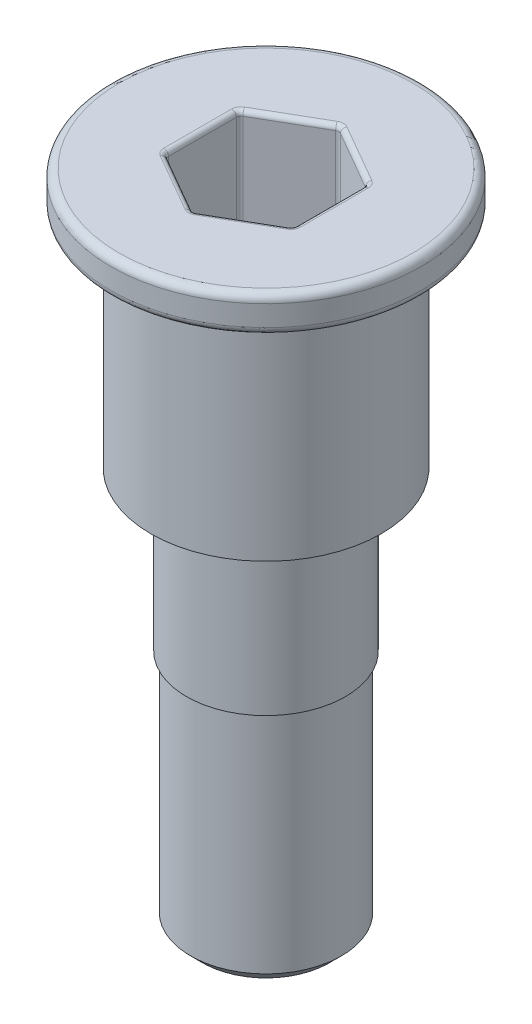
SolidWorks part; units mm, degrees
ref_plane "Plano frontal" through (0, 0, 0) normal (0, 0, 1) x (1, 0, 0)
ref_plane "Plano superior" through (0, 0, 0) normal (0, 1, 0) x (1, 0, 0)
ref_plane "Plano direito" through (0, 0, 0) normal (1, 0, 0) x (0, 0, -1)
sketch "Esboço1" plane through (0, 0, 0) normal (0, 0, 1) x (1, 0, 0)
  line L0 (0, -39.8088) -> (0, 49.1334) construction
  line L1 (0, 17.0567) -> (9.75, 17.0567)
  line L2 (9.75, 17.0567) -> (9.75, 14.7567)
  line L3 (9.75, 14.7567) -> (7.25, 14.7567)
  line L4 (7.25, 14.7567) -> (7.25, 0.7567)
  line L5 (7.25, 0.7567) -> (5, 0.7567)
  line L6 (5, 0.7567) -> (5, -9.2433)
  line L7 (5, -9.2433) -> (4.75, -9.2433)
  line L8 (4.75, -9.2433) -> (4.75, -24.2433)
  line L9 (4.75, -24.2433) -> (0, -24.2433)
  line L10 (0, 17.0567) -> (0, -24.2433)
  dimension "D1" = 4.75
  dimension "D2" = 5
  dimension "D3" = 15
  dimension "D4" = 10
  dimension "D5" = 14
  dimension "D6" = 2.3
  dimension "D7" = 7.25
  dimension "D8" = 9.75
revolve "Revolução1" add sketch "Esboço1" angle 360 about L0
fillet "Filete1" radius 0.5 2 edges at (0, 14.7567, -9.75) (0, 17.0567, -9.75)
sketch "Esboço2" plane through (0, 17.0567, 0) normal (0, 1, 0) x (1, 0, 0)
  line L1 (0, 4.6188) -> (-4, 2.3094)
  line L2 (-4, 2.3094) -> (-4, -2.3094)
  line L3 (-4, -2.3094) -> (0, -4.6188)
  line L4 (0, -4.6188) -> (4, -2.3094)
  line L5 (4, -2.3094) -> (4, 2.3094)
  line L6 (4, 2.3094) -> (0, 4.6188)
  circle A0 centre (0, 0) radius 4 construction
  dimension "D1" = 8
extrude "Corte-extrusão1" cut sketch "Esboço2" against normal blind 6.5
fillet "Filete2" radius 0.3 18 edges at (4, 17.0567, 0) (-2, 17.0567, -3.4641) (2, 17.0567, -3.4641) (-4, 17.0567, 0) (-2, 17.0567, 3.4641) (2, 17.0567, 3.4641) (2, 10.5567, 3.4641) (4, 10.5567, 0) (4, 13.8067, 2.3094) (4, 13.8067, -2.3094) (0, 13.8067, -4.6188) (-4, 13.8067, 2.3094) (-4, 13.8067, -2.3094) (0, 13.8067, 4.6188) (-2, 10.5567, 3.4641) (-4, 10.5567, 0) (2, 10.5567, -3.4641) (-2, 10.5567, -3.4641)
chamfer "Chanfro1" distance 0.75 angle 45 1 edges at (0, -24.2433, -4.75)
